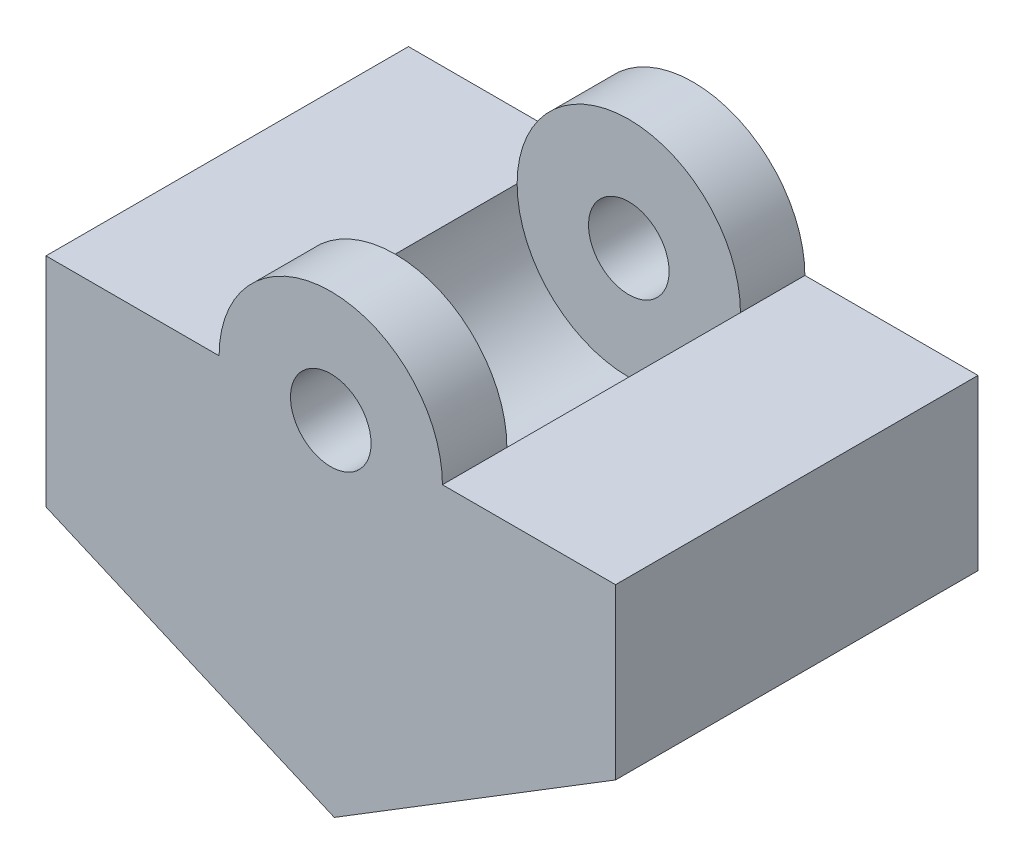
SolidWorks part; units mm, degrees
ref_plane "Front Plane" through (0, 0, 0) normal (0, 0, 1) x (1, 0, 0)
ref_plane "Top Plane" through (0, 0, 0) normal (0, 1, 0) x (1, 0, 0)
ref_plane "Right Plane" through (0, 0, 0) normal (1, 0, 0) x (0, 0, -1)
sketch "Sketch1" plane through (0, 0, 0) normal (0, 0, 1) x (1, 0, 0)
  line L0 (0, 0) -> (-35.7936, 15.4861)
  line L1 (-35.7936, 15.4861) -> (-35.7936, 42.4861)
  line L2 (-35.7936, 42.4861) -> (-14.3013, 42.4861)
  line L3 (34.9192, 42.4861) -> (34.9192, 21.4861)
  line L4 (34.9192, 21.4861) -> (0, 0)
  line L5 (13.4269, 42.4861) -> (34.9192, 42.4861)
  line L6 (-14.3013, 42.4861) -> (13.4269, 42.4861) construction
  arc A0 (13.4269, 42.4861) -> (-14.3013, 42.4861) centre (-0.4372, 42.4861) ccw
  point P7 (0, 0)
  dimension "D1" = 21.4923
  dimension "D2" = 21
  dimension "D3" = 41
  dimension "D4" = 39
  dimension "D5" = 27
  dimension "D6" = 125
extrude "Boss-Extrude1" add sketch "Sketch1" along normal blind 45
sketch "Sketch3" plane through (0, 0, 45) normal (0, 0, 1) x (1, 0, 0)
  line L0 (-14.3013, 42.4861) -> (13.4269, 42.4861) construction
  circle A0 centre (-0.4372, 42.4861) radius 13.8641
extrude "Cut-Extrude1" cut sketch "Sketch3" against normal offset from surface (29 mm away) 8 from offset 8 up to face at (-0.3748, 31.5401, 0) offset against normal yes
sketch "Sketch4" plane through (0, 0, 45) normal (0, 0, 1) x (1, 0, 0)
  line L0 (-14.3013, 42.4861) -> (13.4269, 42.4861) construction
  circle A0 centre (-0.4372, 42.4861) radius 5
  dimension "D1" = 10
extrude "Cut-Extrude2" cut sketch "Sketch4" against normal through all
